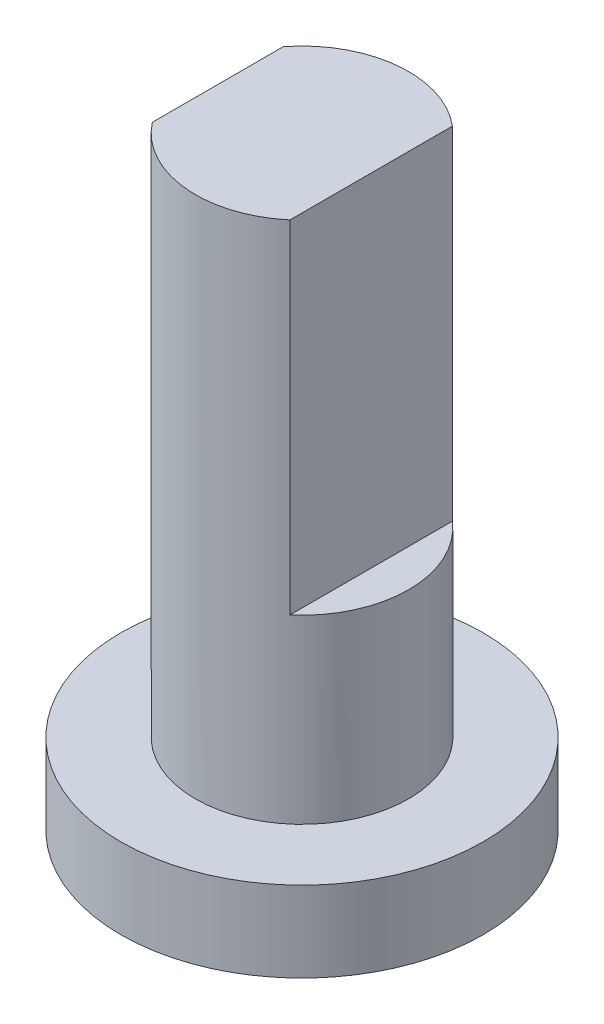
SolidWorks part; units mm, degrees
ref_plane "Front Plane" through (0, 0, 0) normal (0, 0, 1) x (1, 0, 0)
ref_plane "Top Plane" through (0, 0, 0) normal (0, 1, 0) x (1, 0, 0)
ref_plane "Right Plane" through (0, 0, 0) normal (1, 0, 0) x (0, 0, -1)
sketch "Sketch1" plane through (0, 0, 0) normal (0, 1, 0) x (1, 0, 0)
  circle A0 centre (0, 0) radius 4.5
extrude "Boss-Extrude1" add sketch "Sketch1" along normal blind 2
sketch "Sketch2" plane through (0, 2, 0) normal (0, 1, 0) x (1, 0, 0)
  circle A0 centre (0, 0) radius 2.65
  dimension "D1" = 5.3
extrude "Boss-Extrude2" add sketch "Sketch2" along normal blind 4.5
sketch "Sketch4" plane through (0, 6.5, 0) normal (0, 1, 0) x (1, 0, 0)
  line L0 (0, 2.65) -> (0, -2.65) construction
  line L1 (-2.65, 0) -> (2.65, 0) construction
  line L2 (1.7187, -2.017) -> (1.7187, 2.017)
  line L3 (-2.0913, 1.6276) -> (-2.0913, -1.6276)
  circle A0 centre (0, 0) radius 2.65 construction
  circle A1 centre (0, 0) radius 2.65 construction
  arc A2 (-2.0913, -1.6276) -> (1.7187, -2.017) centre (0, 0) ccw
  arc A3 (1.7187, 2.017) -> (-2.0913, 1.6276) centre (0, 0) ccw
  point P7 (0, 0)
  point P11 (0, 0)
  point P16 (1.7187, 0)
  dimension "D1" = 3.81
extrude "Boss-Extrude3" add sketch "Sketch4" along normal blind 8.5
